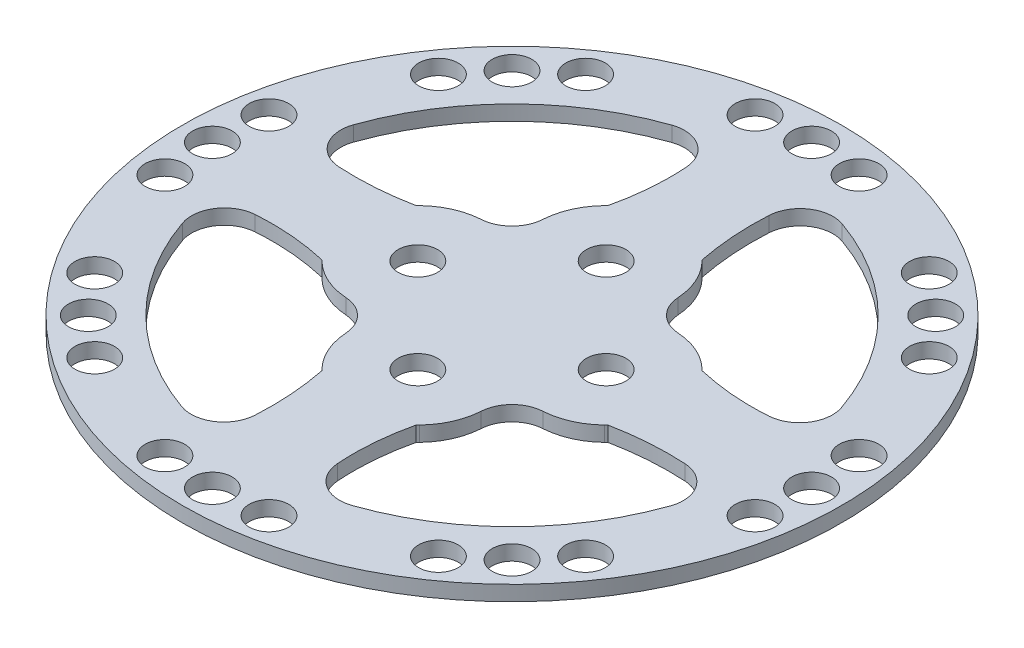
SolidWorks part; units mm, degrees
ref_plane "Front Plane" through (0, 0, 0) normal (0, 0, 1) x (1, 0, 0)
ref_plane "Top Plane" through (0, 0, 0) normal (0, 1, 0) x (1, 0, 0)
ref_plane "Right Plane" through (0, 0, 0) normal (1, 0, 0) x (0, 0, -1)
sketch "Sketch1" plane through (0, 0, 0) normal (0, 1, 0) x (1, 0, 0)
  line L0 (0, 0) -> (-2.8, 0) construction
  line L1 (0, 0) -> (-2.8, 0) construction
  line L2 (0, 0) -> (-2.8, 0) construction
  line L11 (-31.4245, 5) -> (-31.8198, 5)
  line L13 (-31.4245, -5) -> (-31.8198, -5)
  line L15 (-5, 31.4245) -> (-5, 31.8198)
  line L16 (5, 31.4245) -> (5, 31.8198)
  line L17 (31.4245, 5) -> (31.8198, 5)
  line L18 (31.4245, -5) -> (31.8198, -5)
  line L19 (5, -31.4245) -> (5, -31.8198)
  line L20 (-5, -31.4245) -> (-5, -31.8198)
  line L21 (-10, 0) -> (-49.687, 0) construction
  line L22 (-10, 0) -> (-31.8198, 0) construction
  line L23 (-10, 0) -> (-31.8198, 0) construction
  line L25 (8.6603, 5) -> (27.0416, 5)
  line L26 (5, 8.6603) -> (5, 27.0416)
  line L27 (8.6603, -5) -> (27.0416, -5)
  line L28 (5, -8.6603) -> (5, -27.0416)
  line L29 (-5, -8.6603) -> (-5, -27.0416)
  line L30 (-8.6603, -5) -> (-27.0416, -5)
  line L31 (-8.6603, 5) -> (-27.0416, 5)
  line L32 (-5, 8.6603) -> (-5, 27.0416)
  circle A0 centre (0, 0) radius 31.8198 construction
  circle A1 centre (0, 0) radius 35
  circle A2 centre (0, 0) radius 27.5
  circle A3 centre (-31.8198, 0) radius 2.1
  circle A4 centre (-31.3364, -5.5255) radius 2.1
  circle A5 centre (-31.3364, 5.5255) radius 2.1
  circle A6 centre (0, 31.8198) radius 2.1
  circle A7 centre (-18.2511, 26.0653) radius 2.1
  circle A8 centre (31.8198, 0) radius 2.1
  circle A9 centre (-26.0653, 18.2511) radius 2.1
  circle A10 centre (0, -31.8198) radius 2.1
  circle A11 centre (5.5255, 31.3364) radius 2.1
  circle A12 centre (-5.5255, 31.3364) radius 2.1
  circle A13 centre (26.0653, 18.2511) radius 2.1
  circle A14 centre (18.2511, 26.0653) radius 2.1
  circle A15 centre (22.5, 22.5) radius 2.1
  circle A16 centre (31.8198, 0) radius 2.1
  circle A17 centre (22.5, -22.5) radius 2.1
  circle A18 centre (0, -31.8198) radius 2.1
  circle A19 centre (-22.5, -22.5) radius 2.1
  circle A20 centre (-31.8198, 0) radius 2.1
  circle A21 centre (-22.5, 22.5) radius 2.1
  circle A22 centre (31.3364, -5.5255) radius 2.1
  circle A23 centre (31.3364, 5.5255) radius 2.1
  circle A24 centre (18.2511, -26.0653) radius 2.1
  circle A25 centre (26.0653, -18.2511) radius 2.1
  circle A26 centre (-5.5255, -31.3364) radius 2.1
  circle A27 centre (5.5255, -31.3364) radius 2.1
  circle A28 centre (-26.0653, -18.2511) radius 2.1
  circle A29 centre (-18.2511, -26.0653) radius 2.1
  circle A30 centre (0, 0) radius 10 construction
  arc A35 (5.9592, 5.9592) -> (-5.9592, 5.9592) centre (0, 10) ccw
  arc A38 (5.9592, -5.9592) -> (5.9592, 5.9592) centre (10, 0) ccw
  arc A40 (-5.9592, -5.9592) -> (5.9592, -5.9592) centre (0, -10) ccw
  arc A42 (-5.9592, 5.9592) -> (-5.9592, -5.9592) centre (-10, 0) ccw
  point P8 (-15.9099, 0)
  point P23 (0, 0)
  point P29 (0, 0)
  point P36 (0, 0)
  point P43 (0, 0)
  point P44 (0, 0)
  point P68 (0, 0)
  point P71 (0, 0)
  point P74 (0, 0)
  point P85 (0, 0)
  point P96 (0, 0)
  point P102 (0, 0)
  point P112 (0, 0)
  dimension "D1" = 63.6396
  dimension "D2" = 4
  dimension "D3" = 70
  dimension "D5" = 8
  dimension "D8" = 2
  dimension "D9" = 2
  dimension "D10" = 8
extrude "Boss-Extrude1" add sketch "Sketch1" along normal blind 1.6
sketch "Sketch8" plane through (0, 1.6, 0) normal (0, 1, 0) x (1, 0, 0)
  circle A0 centre (0, 0) radius 10 construction
  circle A1 centre (-10, 0) radius 2.1
  circle A2 centre (0, 10) radius 2.1
  circle A3 centre (10, 0) radius 2.1
  circle A4 centre (0, -10) radius 2.1
  point P14 (0, 0)
  dimension "D1" = 4
extrude "Cut-Extrude7" cut sketch "Sketch8" against normal through all
sketch "Sketch10" plane through (0, 1.6, 0) normal (0, 1, 0) x (1, 0, 0)
  line L0 (-5, 27.0416) -> (-27.0416, 5)
  line L1 (-15.1807, 5) -> (-5, 15.1807)
  line L2 (27.0416, 5) -> (5, 27.0416)
  line L3 (5, 15.1807) -> (15.1807, 5)
  line L4 (5, -27.0416) -> (27.0416, -5)
  line L5 (15.1807, -5) -> (5, -15.1807)
  line L6 (-27.0416, -5) -> (-5, -27.0416)
  line L7 (-5, -15.1807) -> (-15.1807, -5)
  spline S0 degree 2 poles (-27.0416, 5) (-21.1112, 3.8214) (-15.1807, 5) knots 0 0 0 1 1 1
  spline S1 degree 2 poles (-5, 15.1807) (-3.6161, 21.1112) (-5, 27.0416) knots 0 0 0 1 1 1
  spline S2 degree 2 poles (5, 27.0416) (3.8214, 21.1112) (5, 15.1807) knots 0 0 0 1 1 1
  spline S3 degree 2 poles (15.1807, 5) (21.1112, 3.6161) (27.0416, 5) knots 0 0 0 1 1 1
  spline S4 degree 2 poles (27.0416, -5) (21.1112, -3.8214) (15.1807, -5) knots 0 0 0 1 1 1
  spline S5 degree 2 poles (5, -15.1807) (3.6161, -21.1112) (5, -27.0416) knots 0 0 0 1 1 1
  spline S6 degree 2 poles (-5, -27.0416) (-3.8214, -21.1112) (-5, -15.1807) knots 0 0 0 1 1 1
  spline S7 degree 2 poles (-15.1807, -5) (-21.1112, -3.6161) (-27.0416, -5) knots 0 0 0 1 1 1
  point P31 (0, 0)
  dimension "D1" = 4
extrude "Cut-Extrude8" cut sketch "Sketch10" against normal blind 1.6
fillet "Fillet2" radius 3.5 12 edges at (5.9592, 0.8, -5.9592) (5.9592, 0.8, 5.9592) (-5.9592, 0.8, 5.9592) (-5.9592, 0.8, -5.9592) (-5, 0.8, -27.0416) (5, 0.8, -27.0416) (27.0416, 0.8, -5) (27.0416, 0.8, 5) (5, 0.8, 27.0416) (-5, 0.8, 27.0416) (-27.0416, 0.8, 5) (-27.0416, 0.8, -5)
